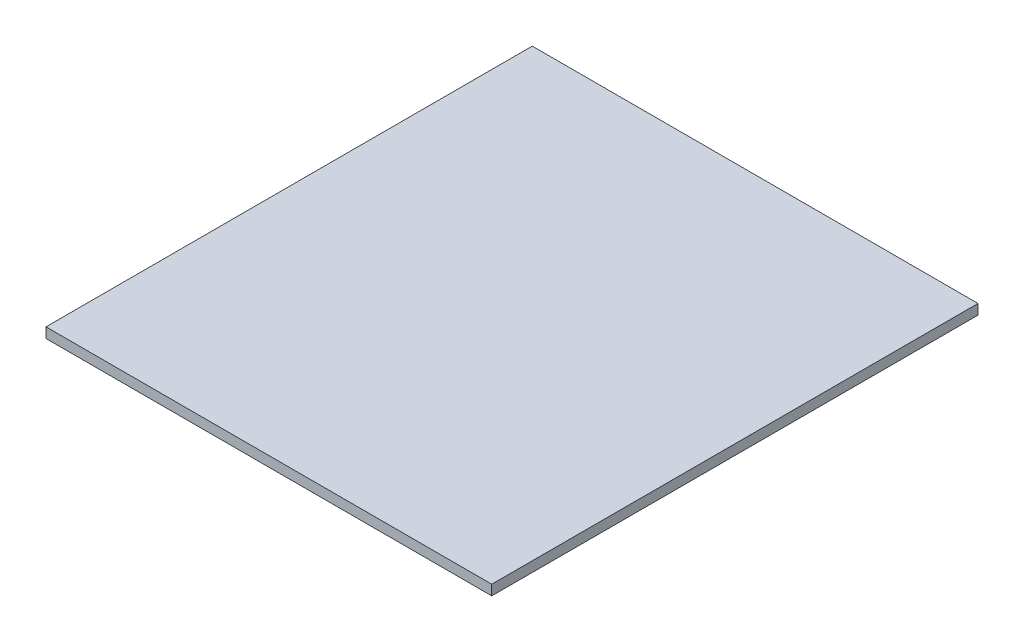
SolidWorks part; units mm, degrees
material "ASTM A36 Steel"
ref_plane "Front Plane" through (0, 0, 0) normal (0, 0, 1) x (1, 0, 0)
ref_plane "Top Plane" through (0, 0, 0) normal (0, 1, 0) x (1, 0, 0)
ref_plane "Right Plane" through (0, 0, 0) normal (1, 0, 0) x (0, 0, -1)
sketch "Sketch1" plane through (0, 0, 0) normal (0, 1, 0) x (1, 0, 0)
  line L1 (-139.7, -152.4) -> (139.7, -152.4)
  line L2 (-139.7, -152.4) -> (-139.7, 152.4)
  line L3 (-139.7, 152.4) -> (139.7, 152.4)
  line L4 (139.7, -152.4) -> (139.7, 152.4)
  line L5 (-139.7, -152.4) -> (139.7, 152.4) construction
  line L6 (-139.7, 152.4) -> (139.7, -152.4) construction
  line L7 (-139.7, 0) -> (139.7, 0) construction
  point P0 (0, 0)
  dimension "D1" = 279.4
  dimension "D2" = 304.8
extrude "Boss-Extrude1" add sketch "Sketch1" along normal blind 6.35
